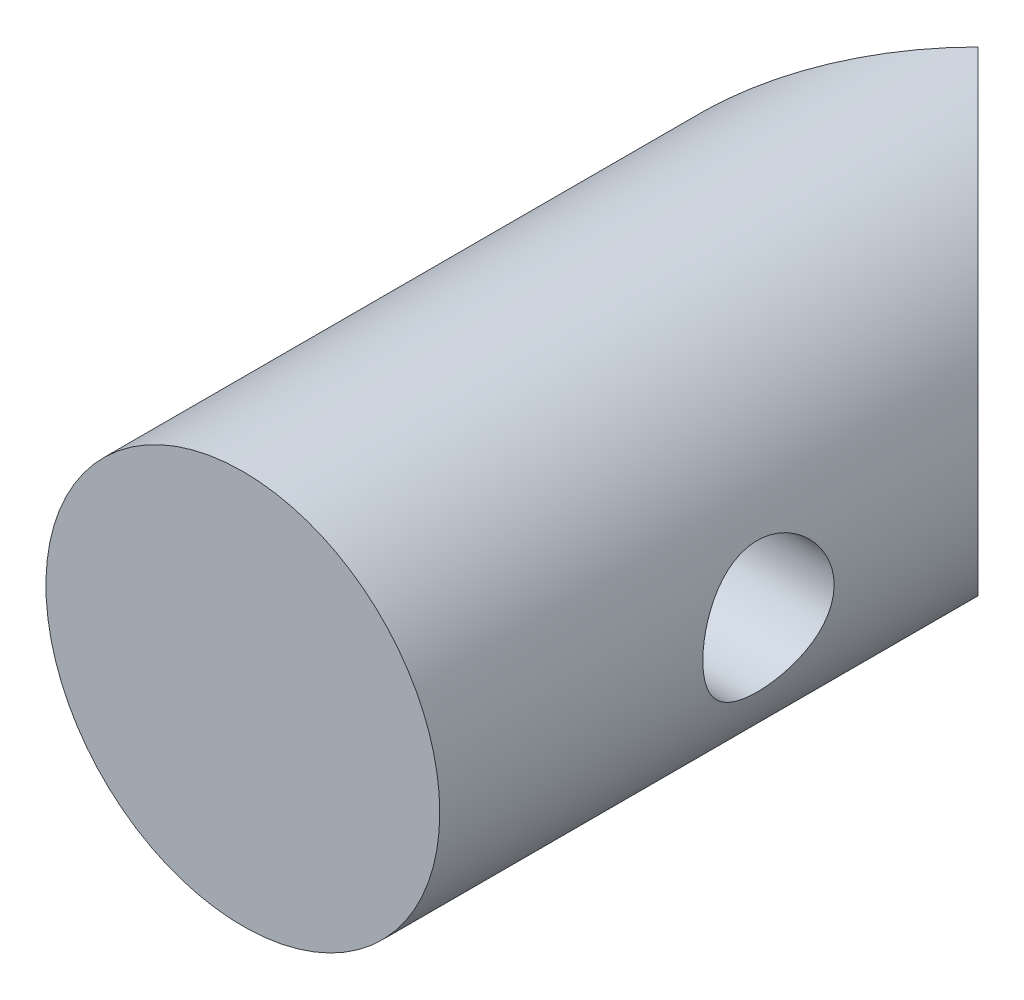
SolidWorks part; units mm, degrees
material "Alloy Steel"
ref_plane "Front Plane" through (0, 0, 0) normal (0, 0, 1) x (1, 0, 0)
ref_plane "Top Plane" through (0, 0, 0) normal (0, 1, 0) x (1, 0, 0)
ref_plane "Right Plane" through (0, 0, 0) normal (1, 0, 0) x (0, 0, -1)
sketch "Sketch1" plane through (0, 0, 0) normal (0, 0, 1) x (1, 0, 0)
  circle A0 centre (0, 0) radius 4.7625
  dimension "D1" = 9.525
extrude "Extrude1" add sketch "Sketch1" along normal blind 17.78
sketch "Sketch2" plane through (0, 0, 0) normal (0, 1, 0) x (1, 0, 0)
  line L0 (0, 0) -> (4.7625, -4.7625)
  line L1 (4.7625, -17.78) -> (4.7625, 0) construction
  line L2 (4.7625, -4.7625) -> (4.7625, 1.9052)
  line L3 (4.7625, 1.9052) -> (-4.7625, 1.9052)
  line L4 (-4.7625, 1.9052) -> (-4.7625, -4.7625)
  line L5 (-4.7625, 0) -> (-4.7625, -17.78) construction
  line L6 (-4.7625, -4.7625) -> (0, 0)
  dimension "D1" = 90
extrude "Extrude2" cut sketch "Sketch2" against normal through all and the other way through all
sketch "Sketch3" plane through (0, 0, 0) normal (1, 0, 0) x (0, 0, -1)
  line L0 (0, 0) -> (-9.8298, 0) construction
  dimension "D1" = 9.8298
hole_wizard "1/8 (0.125) Diameter Hole1" positions "Sketch6" profile "Sketch5" hole size "1/8" standard "Ansi Inch"
sketch "Sketch6" plane through (0, 0, 0) normal (1, 0, 0) x (0, 0, -1)
  point P1 (-9.8298, 0)
sketch "Sketch5" plane through (0, 0, 9.8298) normal (0, 1, 0) x (0, 0, 1)
  line L0 (0, 0) -> (0, 16.9559)
  line L1 (0, 16.9559) -> (1.5875, 16.002)
  line L2 (1.5875, 16.002) -> (1.5875, 0)
  line L5 (1.5875, 0) -> (0, 0)
  line L10 (0, 16.9559) -> (-1.5875, 16.002) construction
  line L11 (0, -6.35) -> (0, 107.95) construction
  dimension "Hole Dia." = 3.175
  dimension "Hole Depth" = 16.002
  dimension "Drill Angle" = 118
sketch "Sketch8" plane through (0, 0, 17.78) normal (0, 0, 1) x (1, 0, 0)
  line L0 (0, 0) -> (-4.7625, 0) construction
  circle A0 centre (0, 0) radius 4.7625 construction
ref_plane "Plane2" through (-4.7625, 0, 17.78) normal (-1, 0, 0) x (0, 0, 1)
sketch "Sketch9" plane through (-4.7625, 0, 17.78) normal (-1, 0, 0) x (0, 0, 1)
  line L0 (0, 0) -> (-9.8298, 0) construction
  dimension "D1" = 9.8298
